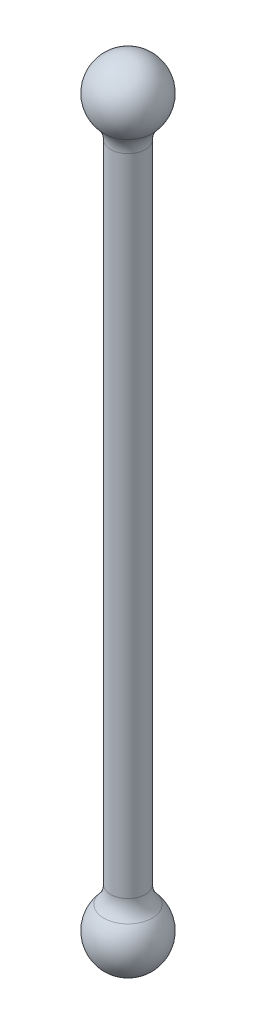
SolidWorks part; units mm, degrees
ref_plane "Front Plane" through (0, 0, 0) normal (0, 0, 1) x (1, 0, 0)
ref_plane "Top Plane" through (0, 0, 0) normal (0, 1, 0) x (1, 0, 0)
ref_plane "Right Plane" through (0, 0, 0) normal (1, 0, 0) x (0, 0, -1)
sketch "Sketch1" plane through (0, 0, 0) normal (0, 0, 1) x (1, 0, 0)
  line L0 (0, 6.75) -> (0, -73.25)
  line L1 (0, -73.25) -> (3.5, -73.25)
  line L2 (3.5, -73.25) -> (3.5, -8.1125)
  arc A0 (4.883, -4.6604) -> (0, 6.75) centre (0, 0) ccw
  arc A1 (3.5, -8.1125) -> (4.883, -4.6604) centre (8.5, -8.1125) cw
  dimension "D1" = 13.5
  dimension "D4" = 5
  dimension "D2" = 3.5
  dimension "D3" = 80
revolve "Revolve1" add sketch "Sketch1" angle 360 about L0
mirror "Mirror1" about plane through (0, -73.25, 0) normal (0, 1, 0) of "Revolve1"
